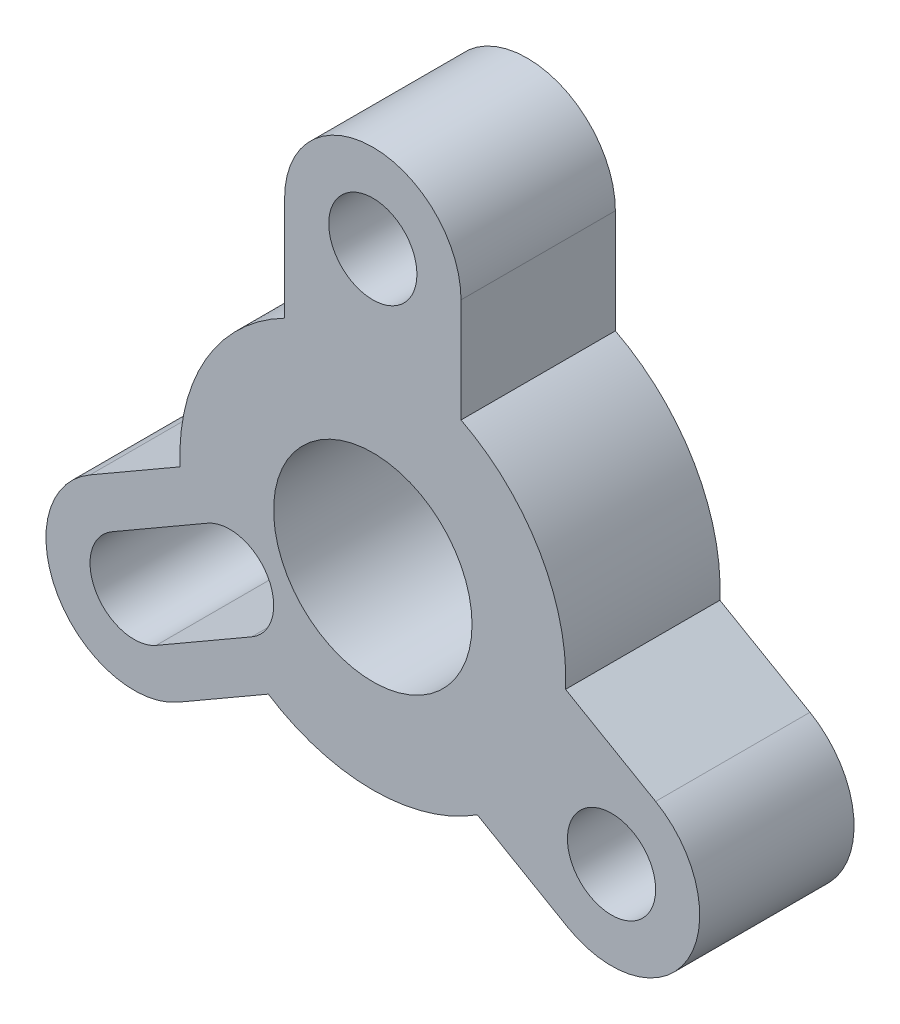
SolidWorks part; units mm, degrees
material "6061 Сплав"
ref_plane "Спереди" through (0, 0, 0) normal (0, 0, 1) x (1, 0, 0)
ref_plane "Сверху" through (0, 0, 0) normal (0, 1, 0) x (1, 0, 0)
ref_plane "Справа" through (0, 0, 0) normal (1, 0, 0) x (0, 0, -1)
sketch "Эскиз1" plane through (0, 0, 0) normal (0, 0, 1) x (1, 0, 0)
  line L0 (-8, 25) -> (-8, 15.5644)
  line L1 (8, 25) -> (8, 15.5644)
  line L2 (17.6506, -19.4282) -> (9.4792, -14.7104)
  line L3 (25.6506, -5.5718) -> (17.4792, -0.854)
  line L4 (-25.6506, -5.5718) -> (-17.4792, -0.854) [skipped]
  line L5 (-17.6506, -19.4282) -> (-9.4792, -14.7104) [skipped]
  line L6 (0, 25) -> (0, 0) construction
  line L7 (0, 0) -> (-42.6372, -24.6166) construction
  line L8 (-14.9904, -4.0359) -> (-23.6506, -9.0359)
  line L9 (-19.6506, -15.9641) -> (-10.9904, -10.9641)
  line L10 (-25.6506, -5.5718) -> (-17.4792, -0.854)
  line L11 (-17.6506, -19.4282) -> (-9.4792, -14.7104)
  circle A0 centre (0, 0) radius 9
  arc A1 (-8, 15.5644) -> (-17.4792, -0.854) centre (0, 0) ccw
  circle A2 centre (0, 25) radius 4
  circle A3 centre (0, 0) radius 25 construction
  circle A4 centre (21.6506, -12.5) radius 4
  arc A5 (17.6506, -19.4282) -> (25.6506, -5.5718) centre (21.6506, -12.5) ccw
  arc A6 (8, 25) -> (-8, 25) centre (0, 25) ccw
  circle A7 centre (-21.6506, -12.5) radius 4 [skipped]
  arc A8 (-24.4906, -5.0211) -> (-16.5937, -18.6989) centre (-21.6506, -12.5) ccw [skipped]
  arc A9 (17.4792, -0.854) -> (8, 15.5644) centre (0, 0) ccw
  circle A10 centre (0, 0) radius 15 construction
  arc A11 (-23.6506, -9.0359) -> (-19.6506, -15.9641) centre (-21.6506, -12.5) ccw
  arc A12 (-10.9904, -10.9641) -> (-14.9904, -4.0359) centre (-12.9904, -7.5) ccw
  arc A13 (-25.6506, -5.5718) -> (-17.6506, -19.4282) centre (-21.6506, -12.5) ccw
  arc A15 (-9.4792, -14.7104) -> (9.4792, -14.7104) centre (0, 0) ccw
  point P14 (0, 0)
  point P32 (0, 0)
  dimension "D1" = 9
  dimension "D2" = 17.5
  dimension "D3" = 25
  dimension "D4" = 8
  dimension "D6" = 16
  dimension "D7" = 15
  dimension "D9" = 4
  dimension "D10" = 8
  dimension "D11" = 16
  dimension "D8" = 120
  dimension "D5" = 3
extrude "Бобышка-Вытянуть1" add sketch "Эскиз1" along normal blind 14
